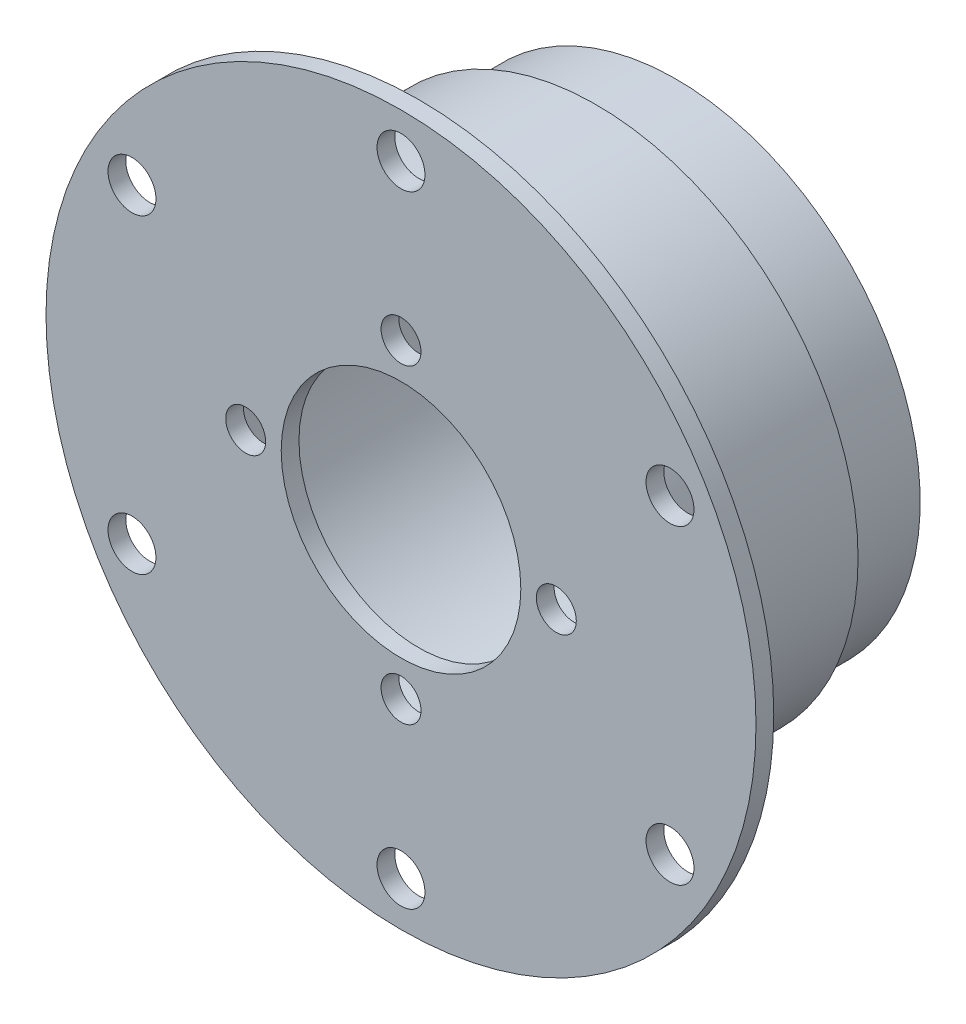
SolidWorks part; units mm, degrees
material "6061-T6 (SS)"
ref_plane "前视基准面" through (0, 0, 0) normal (0, 0, 1) x (1, 0, 0)
ref_plane "上视基准面" through (0, 0, 0) normal (0, 1, 0) x (1, 0, 0)
ref_plane "右视基准面" through (0, 0, 0) normal (1, 0, 0) x (0, 0, -1)
sketch "草图1" plane through (0, 0, 0) normal (0, 0, 1) x (1, 0, 0)
  circle A0 centre (0, 0) radius 13.5
  circle A2 centre (0, 0) radius 40
  dimension "D1" = 27
  dimension "D2" = 80
extrude "凸台-拉伸1" add sketch "草图1" along normal blind 2
sketch "草图2" plane through (0, 0, 2) normal (0, 0, 1) x (1, 0, 0)
  circle A0 centre (0, 0) radius 17.5
  circle A1 centre (0, 17.5) radius 3.1441
  circle A2 centre (17.5, 0) radius 4.9241
  circle A3 centre (0, -17.5) radius 4.4769
  circle A4 centre (-17.5, 0) radius 6.6795
  dimension "D1" = 35
hole_wizard "M4 间隙孔1" positions "3D草图1" profile "草图3" hole size "M4" standard "GB" end condition through all
sketch3d "3D草图1"
  point P0 (-17.5, 0, 2)
  point P3 (0, 17.5, 2)
  point P6 (17.5, 0, 2)
  point P9 (0, -17.5, 2)
sketch "草图3" plane through (-17.5, 0, 2) normal (1, 0, 0) x (0, -1, 0)
  line L0 (0, 0) -> (0, 2)
  line L1 (0, 2) -> (2.25, 2)
  line L2 (2.25, 2) -> (2.25, 0)
  line L5 (2.25, 0) -> (0, 0)
  line L11 (0, -6.35) -> (0, 107.95) construction
  dimension "通孔孔直径" = 4.5
  dimension "通孔孔深度" = 2
hole_wizard "Ø5.4 (5.4) 直径孔1" positions "草图6" profile "草图7" hole size "Ø5.4" standard "GB" end condition through all
sketch "草图6" plane through (0, 0, 0) normal (0, 0, -1) x (-1, 0, 0)
  line L0 (0, 0) -> (0, 50000) construction
  line L1 (0.5537, 0) -> (50000.5537, 0) construction
  circle A0 centre (0, 0) radius 35
  point P18 (0, 35)
  point P28 (30.3109, 17.5)
  point P29 (30.3109, -17.5)
  point P30 (0, -35)
  point P31 (-30.3109, -17.5)
  point P32 (-30.3109, 17.5)
  dimension "D1" = 70
  dimension "D2" = 6
sketch "草图7" plane through (30.3109, 17.5, 0) normal (1, 0, 0) x (0, 1, 0)
  line L0 (0, 0) -> (0, 2)
  line L1 (0, 2) -> (2.7, 2)
  line L2 (2.7, 2) -> (2.7, 0)
  line L5 (2.7, 0) -> (0, 0)
  line L11 (0, -6.35) -> (0, 107.95) construction
  dimension "通孔孔直径" = 5.4
  dimension "通孔孔深度" = 2
sketch "草图8" plane through (0, 0, 0) normal (0, 0, -1) x (-1, 0, 0)
  circle A0 centre (0, 0) radius 21.5
  circle A1 centre (0, 0) radius 29.5
  dimension "D1" = 43
  dimension "D2" = 59
extrude "凸台-拉伸2" add sketch "草图8" along normal blind 29
sketch "草图10" plane through (0, 0, -29) normal (0, 0, -1) x (-1, 0, 0)
  circle A0 centre (0, 0) radius 27.5
  circle A1 centre (0, 0) radius 29.5
  dimension "D1" = 55
  dimension "D2" = 59
extrude "切除-拉伸2" cut sketch "草图10" against normal blind 9
sketch "草图11" plane through (0, 0, -29) normal (0, 0, -1) x (-1, 0, 0)
  line L0 (-25, 0) -> (25, 0) construction
  line L1 (0, 25) -> (0, -25) construction
  circle A0 centre (0, 0) radius 25 construction
  dimension "D1" = 50
hole_wizard "M3 螺纹孔1" positions "3D草图4" profile "草图14" tap size "M3" standard "GB"
sketch3d "3D草图4"
  point P0 (25, 0, -29)
  point P3 (0, 25, -29)
  point P6 (-25, 0, -29)
  point P9 (0, -25, -29)
cosmetic thread "孔螺蚊线1" parameters "D1"=6, "D2"=3
cosmetic thread "孔螺蚊线2" parameters "D1"=6, "D2"=3
cosmetic thread "孔螺蚊线3" parameters "D1"=6, "D2"=3
cosmetic thread "孔螺蚊线4" parameters "D1"=6, "D2"=3
sketch "草图14" plane through (25, 0, -29) normal (1, 0, 0) x (0, 1, 0)
  line L0 (0, 0) -> (0, 9.2511)
  line L1 (0, 9.2511) -> (1.25, 8.5)
  line L2 (1.25, 8.5) -> (1.25, 0)
  line L5 (1.25, 0) -> (0, 0)
  line L10 (0, 9.2511) -> (-1.25, 8.5) construction
  line L11 (0, -6.35) -> (0, 107.95) construction
  dimension "螺纹孔钻头直径" = 2.5
  dimension "螺纹孔钻头深度" = 8.5
  dimension "导头角度" = 118
